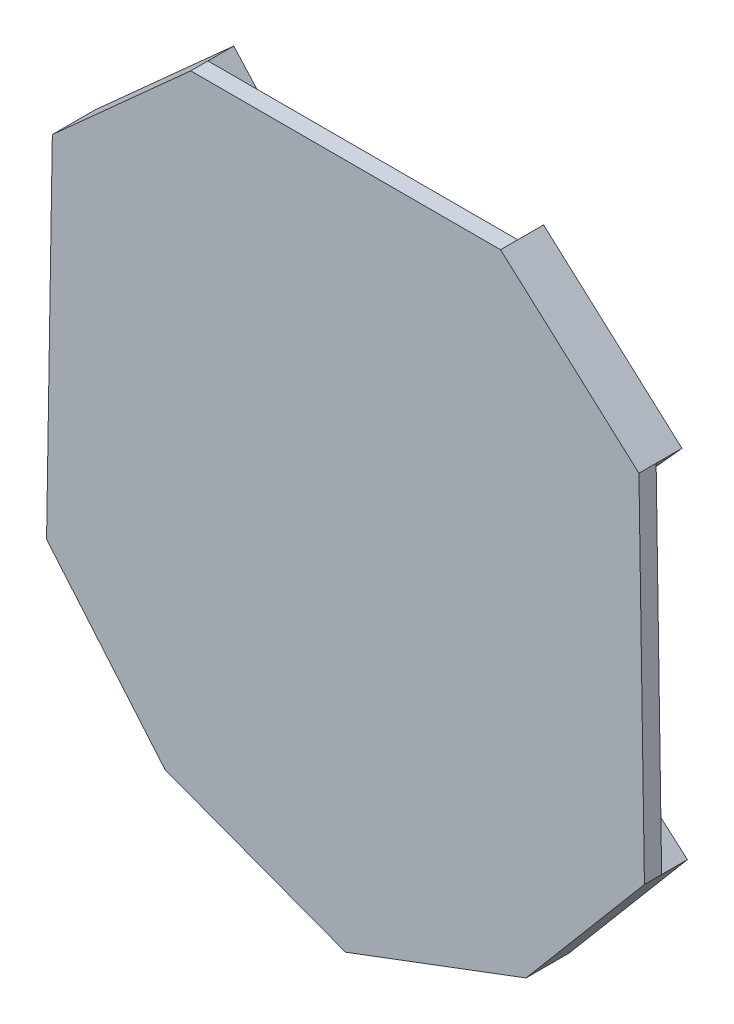
SolidWorks part; units mm, degrees
ref_plane "Plan de face" through (0, 0, 0) normal (0, 0, 1) x (1, 0, 0)
ref_plane "Plan de dessus" through (0, 0, 0) normal (0, 1, 0) x (1, 0, 0)
ref_plane "Plan de droite" through (0, 0, 0) normal (1, 0, 0) x (0, 0, -1)
sketch "Esquisse1" plane through (0, 0, 0) normal (0, 0, 1) x (1, 0, 0)
  line L96 (-176.8003, -47.3393) -> (-184.8437, -54.5668)
  line L97 (-184.8437, -54.5668) -> (-181.1184, -58.7127)
  line L98 (-181.1184, -58.7127) -> (-173.075, -51.4852)
  line L99 (-167.7972, -50.1766) -> (-183.2082, -64.014) construction
  line L100 (-173.075, -51.4852) -> (-176.8003, -47.3393)
  line L101 (-162.5193, -51.4852) -> (-158.7941, -47.3393)
  line L102 (-158.7941, -47.3393) -> (-150.7506, -54.5668)
  line L103 (-150.7506, -54.5668) -> (-154.4759, -58.7127)
  line L104 (-154.4759, -58.7127) -> (-162.5193, -51.4852)
  line L105 (-167.7972, -50.8486) -> (-182.0221, -63.6209)
  line L106 (-182.0221, -63.6209) -> (-173.354, -64.4178)
  line L107 (-173.354, -64.4178) -> (-167.7972, -59.4284)
  line L108 (-162.2403, -64.4178) -> (-167.7972, -59.4284)
  line L109 (-183.2082, -64.014) -> (-173.1824, -64.9357) construction
  line L129 (-153.5722, -63.6209) -> (-162.2403, -64.4178)
  line L130 (-167.7972, -50.8486) -> (-153.5722, -63.6209)
  line L131 (-150.4311, -75.1084) -> (-153.6882, -72.2663)
  line L138 (-153.6882, -72.2663) -> (-160.0623, -80.9367)
  line L139 (-160.0623, -80.9367) -> (-157.3149, -83.2576)
  line L143 (-157.3149, -83.2576) -> (-150.4311, -75.1084)
  line L154 (-153.3345, -66.3639) -> (-162.0558, -67.1657)
  line L155 (-162.0558, -67.1657) -> (-167.8052, -75.6818)
  line L156 (-173.5546, -67.1657) -> (-167.8052, -75.6818)
  line L157 (-182.276, -66.3639) -> (-173.5546, -67.1657)
  line L158 (-182.276, -66.3639) -> (-167.8052, -87.2016)
  line L159 (-153.3345, -66.3639) -> (-167.8052, -87.2016)
  line L160 (-181.9222, -72.2663) -> (-175.5481, -80.9367)
  line L161 (-175.5481, -80.9367) -> (-178.2956, -83.2576)
  line L162 (-178.2956, -83.2576) -> (-185.1793, -75.1084)
  line L163 (-185.1793, -75.1084) -> (-181.9222, -72.2663)
  line L180 (-173.1824, -64.9357) -> (-167.7972, -60.1004) construction
  line L186 (-183.2987, -65.7677) -> (-173.2729, -66.6895) construction
  line L187 (-173.2729, -66.6895) -> (-167.8052, -74.7882) construction
  line L197 (-183.2987, -65.7677) -> (-167.8052, -88.0782) construction
  line L198 (-181.8414, -71.5322) -> (-174.8684, -81.0171) construction
  line L199 (-174.8684, -81.0171) -> (-178.3549, -83.9622) construction
  line L246 (-178.3549, -83.9622) -> (-185.8788, -75.0552) construction
  line L247 (-185.8788, -75.0552) -> (-181.8414, -71.5322) construction
  line L248 (-176.7625, -46.6332) -> (-185.5498, -54.5291) construction
  line L249 (-185.5498, -54.5291) -> (-181.1562, -59.4188) construction
  line L250 (-181.1562, -59.4188) -> (-172.3689, -51.5229) construction
  line L260 (-172.3689, -51.5229) -> (-176.7625, -46.6332) construction
  line L375 (-167.7972, -50.1766) -> (-152.3861, -64.014) construction
  line L376 (-162.4119, -64.9357) -> (-167.7972, -60.1004) construction
  line L377 (-162.3376, -66.6895) -> (-167.8052, -74.7882) construction
  line L378 (-152.3118, -65.7677) -> (-167.8052, -88.0782) construction
  line L379 (-163.2254, -51.5229) -> (-158.8318, -46.6332) construction
  line L380 (-154.4381, -59.4188) -> (-163.2254, -51.5229) construction
  line L381 (-150.0445, -54.5291) -> (-154.4381, -59.4188) construction
  line L382 (-158.8318, -46.6332) -> (-150.0445, -54.5291) construction
  line L383 (-149.7316, -75.0552) -> (-153.7691, -71.5322) construction
  line L384 (-157.2555, -83.9622) -> (-149.7316, -75.0552) construction
  line L385 (-160.742, -81.0171) -> (-157.2555, -83.9622) construction
  line L386 (-153.7691, -71.5322) -> (-160.742, -81.0171) construction
  line L387 (-152.3118, -65.7677) -> (-162.3376, -66.6895) construction
  line L388 (-152.3861, -64.014) -> (-162.4119, -64.9357) construction
  point P203 (-141.5228, -71.3355)
  point P204 (-141.5228, 1.5705)
  dimension "D3" = 0.5
  dimension "D4" = 0.5
  dimension "D6" = 0.5
  dimension "D2" = 0.5
  dimension "D1" = 0.5
  dimension "D5" = 0.5
extrude "Boss.-Extru.1" add sketch "Esquisse1" along normal blind 1.5
sketch "Esquisse2" plane through (0, 0, 1.5) normal (0, 0, 1) x (1, 0, 0)
  line L0 (-176.8003, -47.3393) -> (-158.7941, -47.3393)
  line L1 (-158.7941, -47.3393) -> (-150.7506, -54.5668)
  line L2 (-150.7506, -54.5668) -> (-150.4311, -75.1084)
  line L3 (-150.4311, -75.1084) -> (-157.3149, -83.2576)
  line L4 (-157.3149, -83.2576) -> (-167.8052, -87.2016)
  line L5 (-167.8052, -87.2016) -> (-178.2956, -83.2576)
  line L6 (-178.2956, -83.2576) -> (-185.1793, -75.1084)
  line L7 (-185.1793, -75.1084) -> (-184.8437, -54.5668)
  line L8 (-184.8437, -54.5668) -> (-176.8003, -47.3393)
extrude "Boss.-Extru.2" add sketch "Esquisse2" along normal blind 1
